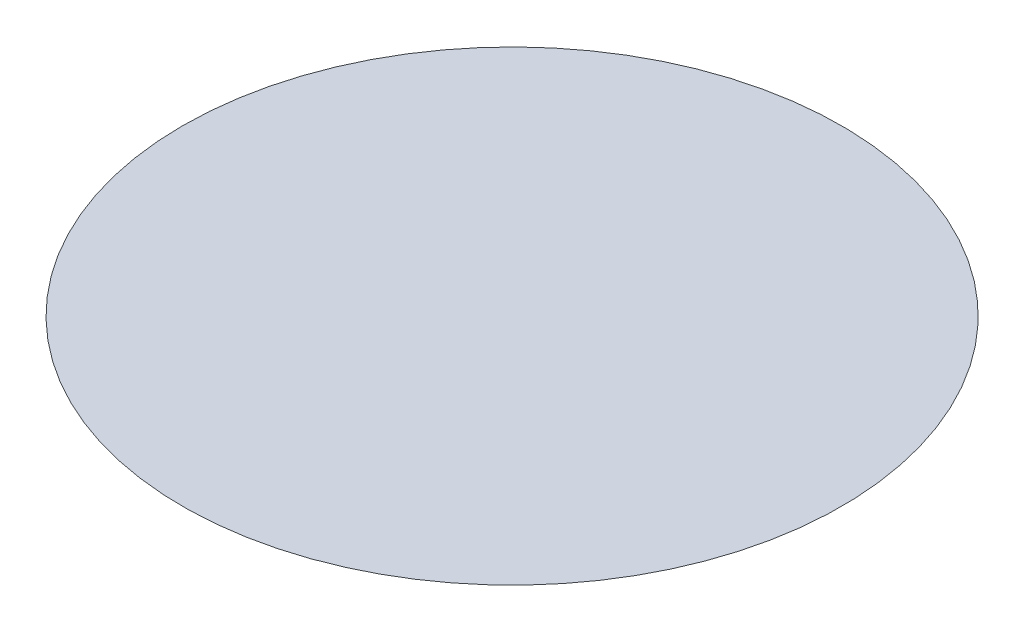
SolidWorks part; units mm, degrees
ref_plane "Спереди" through (0, 0, 0) normal (0, 0, 1) x (1, 0, 0)
ref_plane "Сверху" through (0, 0, 0) normal (0, 1, 0) x (1, 0, 0)
ref_plane "Справа" through (0, 0, 0) normal (1, 0, 0) x (0, 0, -1)
sketch "Эскиз1" plane through (0, 0, 0) normal (0, 0, 1) x (1, 0, 0)
  line L0 (0, 0) -> (0, -1)
  line L1 (0, -1) -> (3.0418, -1)
  line L2 (3.6546, -0.7142) -> (3.7743, -0.5715)
  line L3 (0, 0) -> (2.3757, 0)
  line L4 (0, 0) -> (2.3757, 0) construction
  line L5 (5, 0) -> (2.3757, 0)
  arc A0 (5, 0) -> (3.7743, -0.5715) centre (5, -1.6) ccw
  arc A1 (3.0418, -1) -> (3.6546, -0.7142) centre (3.0418, -0.2) ccw
  dimension "D1" = 1
  dimension "D2" = 130
  dimension "D3" = 1.6
  dimension "D5" = 0.8
  dimension "D4" = 5
revolve "Повернуть1" add sketch "Эскиз1" angle 360 about L0
sketch "Эскиз ориентации" plane through (0, 0, 0) normal (0, 1, 0) x (1, 0, 0)
  circle A0 centre (0, 0) radius 5 construction
  circle A1 centre (0, 0) radius 5
  point P3 (0, 0)
other "Инструмент формы1"
